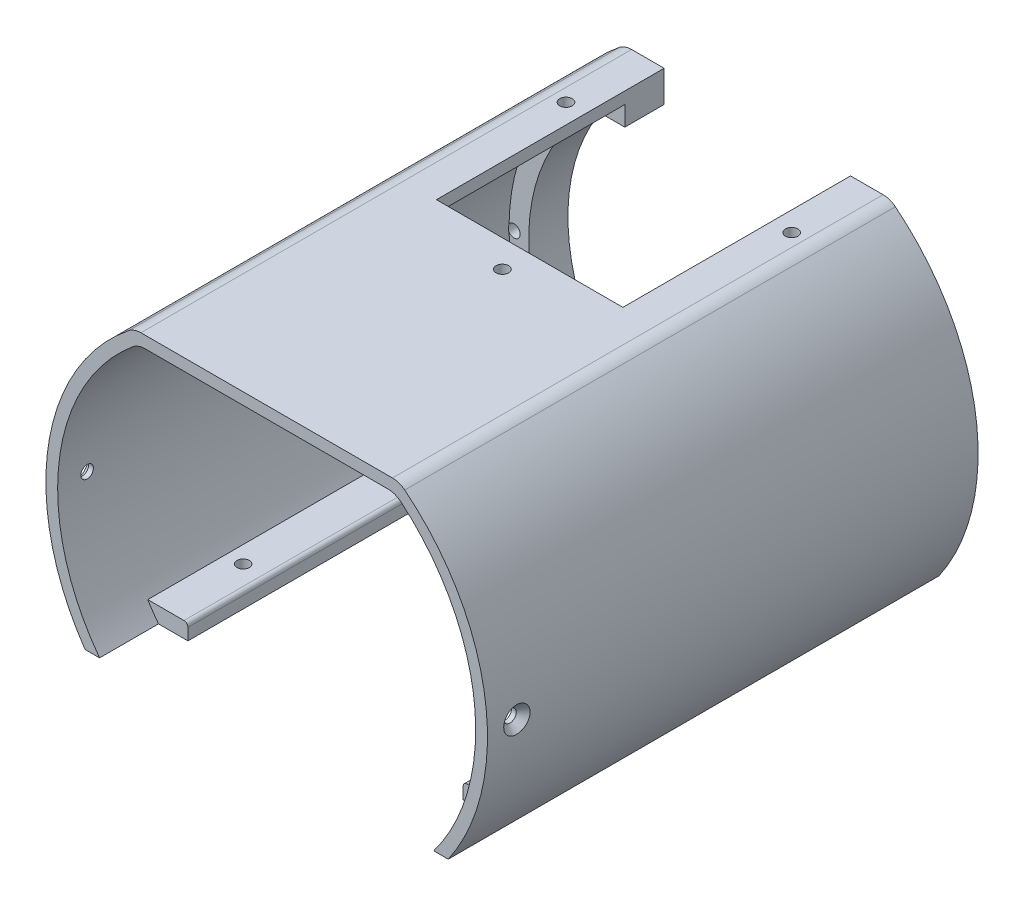
SolidWorks part; units mm, degrees
material "ABS PC"
ref_plane "Ön Düzlem" through (0, 0, 0) normal (0, 0, 1) x (1, 0, 0)
ref_plane "Üst Düzlem" through (0, 0, 0) normal (0, 1, 0) x (1, 0, 0)
ref_plane "Sağ Düzlem" through (0, 0, 0) normal (1, 0, 0) x (0, 0, -1)
sketch "Çizim1" plane through (0, 0, 0) normal (0, 0, 1) x (1, 0, 0)
  line L0 (0, 0) -> (0, 45) construction
  line L1 (32.04, 45) -> (-32.04, 45)
  line L2 (0, 0) -> (0, -45) construction
  line L5 (30.9687, 42) -> (-30.9687, 42)
  line L6 (33.75, 45) -> (-33.75, 45) construction
  line L7 (33.75, -45) -> (-33.75, -45) construction
  line L8 (32.7347, -42) -> (-32.7347, -42) construction
  line L9 (32.7347, 42) -> (-32.7347, 42) construction
  line L10 (0, -42) -> (0, -32) construction
  line L11 (-46.2608, -32) -> (-35.0625, -32)
  line L12 (-35.0625, -32) -> (-35.0625, -28)
  line L13 (-35.0625, -28) -> (-45.2942, -28)
  line L14 (35.0625, -32) -> (35.0625, -28)
  line L15 (35.0625, -28) -> (45.2942, -28)
  line L16 (35.0625, -32) -> (46.2608, -32)
  arc A0 (-35.1659, 43.9024) -> (-46.2608, -32) centre (0, 0) ccw
  arc A1 (46.2608, -32) -> (35.1659, 43.9024) centre (0, 0) ccw
  arc A2 (-34.1779, 40.8342) -> (-45.2942, -28) centre (0, 0) ccw
  arc A3 (45.2942, -28) -> (34.1779, 40.8342) centre (0, 0) ccw
  arc A4 (33.75, -45) -> (33.75, 45) centre (0, 0) ccw construction
  arc A5 (32.04, 45) -> (35.1659, 43.9024) centre (32.04, 40) cw
  arc A6 (-33.75, 45) -> (-33.75, -45) centre (0, 0) ccw construction
  arc A9 (32.7347, -42) -> (32.7347, 42) centre (0, 0) ccw construction
  arc A11 (-32.7347, 42) -> (-32.7347, -42) centre (0, 0) ccw construction
  arc A13 (34.1779, 40.8342) -> (30.9687, 42) centre (30.9687, 37) ccw
  arc A14 (-34.1779, 40.8342) -> (-30.9687, 42) centre (-30.9687, 37) cw
  arc A15 (-32.04, 45) -> (-35.1659, 43.9024) centre (-32.04, 40) ccw
  point P7 (0, 45)
  point P11 (0, -45)
  point P45 (0, -32)
  dimension "D1" = 112.5
  dimension "D4" = 5
  dimension "D2" = 45
  dimension "D5" = 74
  dimension "D6" = 11.1984
  dimension "D7" = 4
  dimension "D3" = 3
extrude "Yükseklik-Ekstrüzyon2" add sketch "Çizim1" along normal mid plane 125
sketch "Çizim3" plane through (0, 0, 62.5) normal (0, 0, 1) x (1, 0, 0)
  line L1 (-42.5625, -32) -> (-42.5625, -32.2836)
  line L3 (-42.5625, -32.2836) -> (-35.0625, -32.2836)
  line L4 (-46.2608, -32) -> (-35.0625, -32) construction
  line L6 (35.0625, -28) -> (45.2942, -28)
  line L7 (35.0625, -28) -> (35.0625, -32)
  line L8 (-35.0625, -32) -> (-35.0625, -28)
  line L9 (-35.0625, -28) -> (-45.2942, -28)
  line L10 (-35.0625, -32.2836) -> (-35.0625, -32)
  line L11 (42.5626, -31.9998) -> (42.5626, -32.4036)
  line L12 (42.5626, -32.4036) -> (35.0625, -32.4036)
  line L13 (35.0625, -32.4036) -> (35.0625, -32)
  arc A0 (42.5626, -31.9998) -> (45.2942, -28) centre (0, 0) ccw
  arc A1 (-45.2942, -28) -> (-42.5625, -32) centre (0, 0) ccw
  point P6 (0.0029, 42.0002)
  point P9 (0, 0)
  point P21 (-32.7315, 42.0025)
extrude "Kes-Ekstrüzyon5" cut sketch "Çizim3" against normal blind 15
sketch "Çizim4" plane through (0, 45, 0) normal (0, 1, 0) x (1, 0, 0)
  line L0 (0, 0) -> (0, 62.5) construction
  line L2 (32.04, 62.5) -> (-32.04, 62.5) construction
  line L3 (23.75, 62.5) -> (-23.75, 62.5)
  line L4 (-23.75, 62.5) -> (-23.75, 4.5)
  line L5 (23.75, 62.5) -> (23.75, 4.5)
  line L6 (-23.75, 4.5) -> (23.75, 4.5)
  point P8 (0, 62.5)
  dimension "D1" = 47.5
  dimension "D2" = 58
extrude "Kes-Ekstrüzyon6" cut sketch "Çizim4" against normal blind 15
sketch "Çizim5" plane through (0, 45, 0) normal (0, 1, 0) x (1, 0, 0)
  line L0 (-23.75, 62.5) -> (-28.75, 62.5) construction
  line L1 (-23.75, 62.5) -> (-32.04, 62.5) construction
  line L2 (-28.75, 62.5) -> (-28.75, 42.5) construction
  line L3 (0, 4.5) -> (0, 72.3668) construction
  line L4 (-23.75, 4.5) -> (23.75, 4.5) construction
  line L5 (23.75, 62.5) -> (28.75, 62.5) construction
  line L6 (28.75, 62.5) -> (28.75, 42.5) construction
  line L7 (0, 4.5) -> (0, -2.45) construction
  point P6 (-28.75, 42.5)
  point P13 (28.75, 42.5)
  point P16 (-28.75, 42.5)
  point P20 (28.75, 42.5)
  point P25 (0, -2.45)
  point P29 (0, -2.45)
  dimension "D1" = 5
  dimension "D2" = 20
  dimension "D3" = 6.95
hole_wizard "M3 Boşluklu Delik1" positions "Çizim5" profile "Çizim6" hole size "M3" standard "ISO"
sketch "Çizim6" plane through (0, 45, 2.45) normal (1, 0, 0) x (0, 0, 1)
  line L0 (0, 0) -> (0, 12.4614)
  line L1 (0, 12.4614) -> (1.6, 11.5)
  line L2 (1.6, 11.5) -> (1.6, 0)
  line L5 (1.6, 0) -> (0, 0)
  line L10 (0, 12.4614) -> (-1.6, 11.5) construction
  line L11 (0, -6.35) -> (0, 107.95) construction
  dimension "Hole Dia." = 3.2
  dimension "Hole Depth" = 11.5
  dimension "Drill Angle" = 118
sketch "Çizim7" plane through (0, -32, 0) normal (0, -1, 0) x (1, 0, 0)
  line L0 (-46.2608, -27.5) -> (-41.0008, -27.5) construction
  line L1 (-46.2608, 62.5) -> (-46.2608, -62.5) construction
  line L2 (-46.2608, -62.5) -> (-35.0625, -62.5) construction
  line L3 (46.2608, -27.5) -> (41.0008, -27.5) construction
  line L4 (46.2608, 62.5) -> (46.2608, -62.5) construction
  line L5 (-46.2608, 27.5) -> (-41.0008, 27.5) construction
  line L6 (-46.2608, 62.5) -> (-42.5625, 62.5) construction
  point P1 (-41.0008, -27.5)
  point P7 (41.0008, -27.5)
  point P11 (-41.0008, 27.5)
  point P14 (41.0008, 27.5)
  point P18 (-41.0008, 27.5)
  point P22 (-41.0008, -27.5)
  point P26 (41.0008, -27.5)
  dimension "D1" = 5.26
  dimension "D2" = 35
  dimension "D3" = 5.26
  dimension "D4" = 5.26
  dimension "D5" = 35
hole_wizard "M3x0.5 Helisarmal İçin Dişli Delik2" positions "Çizim7" profile "Çizim8" tap size "M3x0.5" standard "Helicoil® Metric"
sketch "Çizim8" plane through (41.0008, -32, -27.5) normal (1, 0, 0) x (0, 0, -1)
  line L0 (0, 0) -> (0, 11.9464)
  line L1 (0, 11.9464) -> (1.575, 11)
  line L2 (1.575, 11) -> (1.575, 0)
  line L5 (1.575, 0) -> (0, 0)
  line L10 (0, 11.9464) -> (-1.575, 11) construction
  line L11 (0, -6.35) -> (0, 107.95) construction
  dimension "Tap Drill Dia." = 3.15
  dimension "Tap Drill Depth" = 11
  dimension "Drill Angle" = 118
ref_plane "Düzlem2" through (56.25, 0, 0) normal (-1, 0, 0) x (0, 0, 1)
fillet "Radyus1" radius 1 2 edges at (35.0625, -28, -7.5) (-35.0625, -28, -7.5)
sketch "Çizim14" plane through (0, 0, -62.5) normal (0, 0, -1) x (-1, 0, 0)
  line L53 (36.0625, -23) -> (42.4154, -23)
  line L54 (30.9687, 37) -> (23.75, 37)
  line L55 (36.0625, -23) -> (42.4154, -23)
  line L56 (30.9687, 37) -> (23.75, 37)
  line L60 (36.0625, -29) -> (36.0625, -23)
  line L61 (23.75, 43) -> (23.75, 37)
  line L62 (36.0625, -29) -> (45.8483, -29)
  line L63 (30.9687, 43) -> (23.75, 43)
  line L64 (36.0625, -29) -> (45.8483, -29)
  line L65 (30.9687, 43) -> (23.75, 43)
  line L73 (-23.75, 43) -> (-30.9687, 43)
  line L74 (-45.8483, -29) -> (-36.0625, -29)
  line L75 (-23.75, 43) -> (-30.9687, 43)
  line L76 (-45.8483, -29) -> (-36.0625, -29)
  line L80 (-36.0625, -29) -> (-36.0625, -23)
  line L81 (-23.75, 43) -> (-23.75, 37)
  line L82 (-23.75, 37) -> (-30.9687, 37)
  line L83 (-42.4154, -23) -> (-36.0625, -23)
  line L84 (-23.75, 37) -> (-30.9687, 37)
  line L85 (-42.4154, -23) -> (-36.0625, -23)
  arc A37 (42.4154, -23) -> (30.9687, 37) centre (0, 0) ccw
  arc A38 (42.4154, -23) -> (30.9687, 37) centre (0, 0) ccw
  arc A44 (45.8483, -29) -> (34.8198, 41.601) centre (0, 0) ccw
  arc A45 (34.8198, 41.601) -> (30.9687, 43) centre (30.9687, 37) ccw
  arc A46 (45.8483, -29) -> (34.8198, 41.601) centre (0, 0) ccw
  arc A47 (34.8198, 41.601) -> (30.9687, 43) centre (30.9687, 37) ccw
  arc A53 (-30.9687, 43) -> (-34.8198, 41.601) centre (-30.9687, 37) ccw
  arc A54 (-34.8198, 41.601) -> (-45.8483, -29) centre (0, 0) ccw
  arc A55 (-30.9687, 43) -> (-34.8198, 41.601) centre (-30.9687, 37) ccw
  arc A56 (-34.8198, 41.601) -> (-45.8483, -29) centre (0, 0) ccw
  arc A62 (-30.9687, 37) -> (-42.4154, -23) centre (0, 0) ccw
  arc A63 (-30.9687, 37) -> (-42.4154, -23) centre (0, 0) ccw
  dimension "D1" = 5
  dimension "D2" = 1
  dimension "D3" = 1
  dimension "D4" = 5
extrude "Yükseklik-Ekstrüzyon3" add sketch "Çizim14" against normal blind 10
sketch "Çizim15" plane through (0, 0, -62.5) normal (0, 0, -1) x (-1, 0, 0)
  line L0 (0, 0) -> (-52, 0) construction
  line L1 (0, 0) -> (-36.7696, 36.7696) construction
  line L2 (0, 0) -> (-45.0333, -26) construction
  line L3 (0, 0) -> (52, 0) construction
  line L4 (0, 0) -> (36.7696, 36.7696) construction
  line L5 (0, 0) -> (45.0333, -26) construction
  arc A0 (-36.7696, 36.7696) -> (-45.0333, -26) centre (0, 0) ccw construction
  arc A1 (45.0333, -26) -> (36.7696, 36.7696) centre (0, 0) ccw construction
  point P4 (-52, 0)
  point P5 (-36.7696, 36.7696)
  point P6 (-45.0333, -26)
  point P7 (52, 0)
  point P8 (36.7696, 36.7696)
  point P9 (45.0333, -26)
  point P13 (-36.7696, 36.7696)
  point P17 (-52, 0)
  point P21 (-45.0333, -26)
  point P25 (45.0333, -26)
  point P29 (52, 0)
  point P33 (36.7696, 36.7696)
  dimension "D1" = 104
  dimension "D2" = 45
  dimension "D3" = 30
  dimension "D4" = 45
  dimension "D5" = 30
hole_wizard "M3x0.5 Helisarmal İçin Dişli Delik1" positions "Çizim15" profile "Çizim17" tap size "M3x0.5" standard "Helicoil® Metric"
sketch "Çizim17" plane through (-36.7696, 36.7696, -62.5) normal (1, 0, 0) x (0, 1, 0)
  line L0 (0, 0) -> (0, 10.9464)
  line L1 (0, 10.9464) -> (1.575, 10)
  line L2 (1.575, 10) -> (1.575, 0)
  line L5 (1.575, 0) -> (0, 0)
  line L10 (0, 10.9464) -> (-1.575, 10) construction
  line L11 (0, -6.35) -> (0, 107.95) construction
  dimension "Tap Drill Dia." = 3.15
  dimension "Tap Drill Depth" = 10
  dimension "Drill Angle" = 118
ref_plane "Düzlem3" through (56.25, 0, 0) normal (1, 0, 0) x (0, 0, -1)
sketch "Çizim21" plane through (56.25, 0, 0) normal (1, 0, 0) x (0, 0, -1)
  line L0 (-55, 0) -> (-62.5, 0) construction
  line L1 (-62.5, 43.9024) -> (-62.5, -32) construction
  point P0 (-55, 0)
  point P8 (-55, 0)
  dimension "D1" = 7.5
hole_wizard "M3 Altıgen Alyan Havşa Başlı Kör Vida İçin Havşa3" positions "Çizim21" profile "Çizim22" countersink size "M3" standard "ISO"
sketch "Çizim22" plane through (56.25, 0, 55) normal (0, 1, 0) x (0, 0, -1)
  line L0 (0, 0) -> (0, 9.9614)
  line L1 (0, 9.9614) -> (1.6, 9)
  line L2 (1.6, 9) -> (1.6, 1.76)
  line L3 (1.6, 1.76) -> (3.36, 0)
  line L5 (3.36, 0) -> (0, 0)
  line L6 (-1.6, 1.76) -> (-3.36, 0) construction
  line L10 (0, 9.9614) -> (-1.6, 9) construction
  line L11 (0, -6.35) -> (0, 107.95) construction
  dimension "Hole Dia." = 3.2
  dimension "Hole Depth" = 9
  dimension "Near C'Sink Dia." = 6.72
  dimension "Near C'Sink Angle" = 90
  dimension "Drill Angle" = 118
pattern_circular "Dairesel Kaplama1" count 2 over 180 about axis through (0, 0, 62.5) along (0, 0, 1) of "M3 Altıgen Alyan Havşa Başlı Kör Vida İçin Havşa3"
